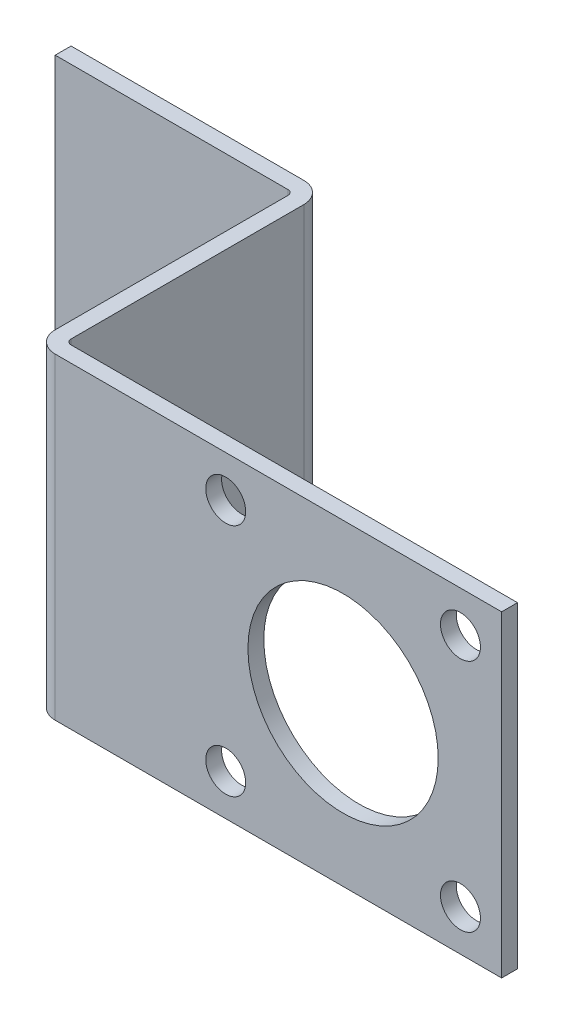
SolidWorks part; units mm, degrees
ref_plane "Front Plane" through (0, 0, 0) normal (0, 0, 1) x (1, 0, 0)
ref_plane "Top Plane" through (0, 0, 0) normal (0, 1, 0) x (1, 0, 0)
ref_plane "Right Plane" through (0, 0, 0) normal (1, 0, 0) x (0, 0, -1)
sketch "Sketch1" plane through (0, 0, 0) normal (0, 0, 1) x (1, 0, 0)
  line L1 (-28.4999, -28.4999) -> (28.4999, -28.4999) construction
  line L2 (-28.4999, -28.4999) -> (-28.4999, 28.4999) construction
  line L3 (-28.4999, 28.4999) -> (28.4999, 28.4999) construction
  line L4 (28.4999, -28.4999) -> (28.4999, 28.4999) construction
  line L5 (-28.4999, -28.4999) -> (28.4999, 28.4999) construction
  line L6 (-28.4999, 28.4999) -> (28.4999, -28.4999) construction
  line L7 (-23.5, -23.5) -> (23.5, -23.5) construction
  line L8 (-23.5, -23.5) -> (-23.5, 23.5) construction
  line L9 (-23.5, 23.5) -> (23.5, 23.5) construction
  line L10 (23.5, -23.5) -> (23.5, 23.5) construction
  line L11 (-23.5, -23.5) -> (23.5, 23.5) construction
  line L12 (-23.5, 23.5) -> (23.5, -23.5) construction
  circle A0 centre (0, 0) radius 19.05
  circle A1 centre (23.5, 23.5) radius 4
  circle A2 centre (23.5, -23.5) radius 4
  circle A3 centre (-23.5, -23.5) radius 4
  circle A4 centre (-23.5, 23.5) radius 4
  dimension "D1" = 38.1
  dimension "D7" = 8
  dimension "D2" = 56.9999
  dimension "D6" = 47
sketch "Sketch2" plane through (0, 0, 0) normal (0, 1, 0) x (1, 0, 0)
  line L0 (31.75, 0) -> (-57.6579, 0)
  line L1 (-61.8489, 4.191) -> (-61.8489, 50.819)
  line L2 (-62.8649, 51.835) -> (-109.4739, 51.835)
  line L3 (31.75, 3.175) -> (-57.6579, 3.175)
  line L4 (-58.6739, 4.191) -> (-58.6739, 50.819)
  line L5 (-62.8649, 55.01) -> (-109.4739, 55.01)
  line L6 (-109.4739, 51.835) -> (-109.4739, 55.01)
  line L7 (31.75, 0) -> (31.75, 3.175)
  line L8 (-28.4999, -10.8428) -> (-28.4999, 10.8428) construction
  arc A0 (-61.8489, 50.819) -> (-62.8649, 51.835) centre (-62.8649, 50.819) ccw
  arc A1 (-57.6579, 0) -> (-61.8489, 4.191) centre (-57.6579, 4.191) cw
  arc A2 (-57.6579, 3.175) -> (-58.6739, 4.191) centre (-57.6579, 4.191) cw
  arc A3 (-58.6739, 50.819) -> (-62.8649, 55.01) centre (-62.8649, 50.819) ccw
  point P19 (-28.4999, 0)
  dimension "D1" = 1.016
  dimension "D2" = 4.191
  dimension "D4" = 55.01
  dimension "D5" = 30.1739
  dimension "D6" = 50.8
  dimension "D7" = 31.75
  dimension "D3" = 3.175
extrude "Boss-Extrude1" add sketch "Sketch2" along normal mid plane 63.5 contours L5 L6 L2 A0 L1 A1 L0 L7 L3 A2 L4 A3
extrude "Cut-Extrude1" cut sketch "Sketch1" against normal through all both and the other way through all
